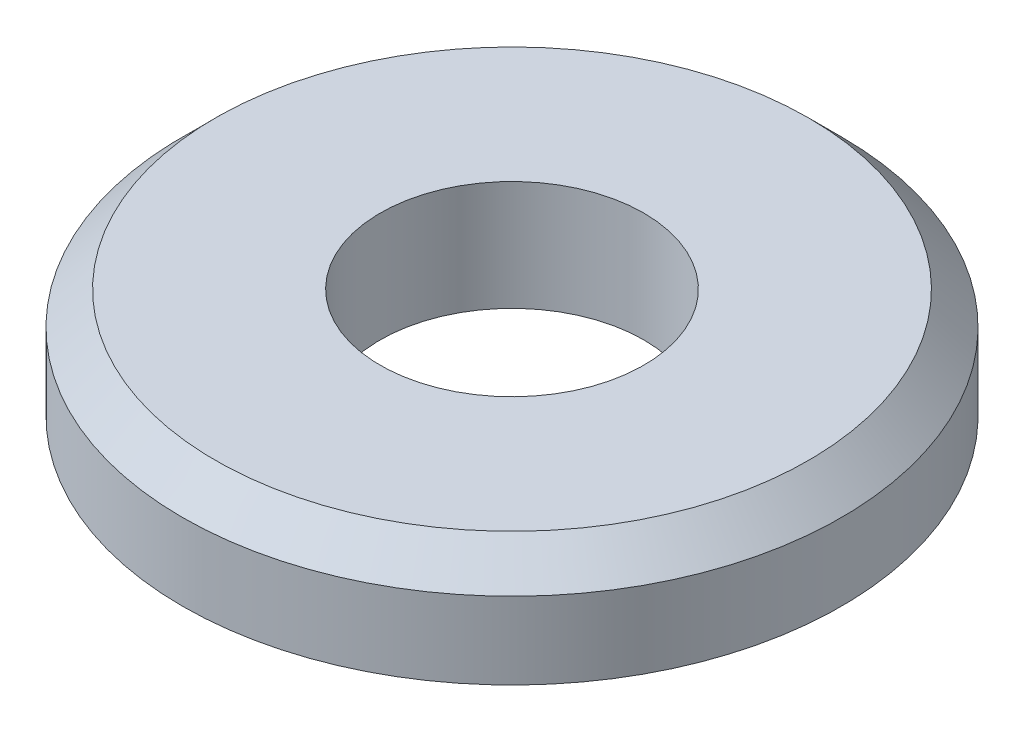
SolidWorks part; units mm, degrees
material "Stainless Steel (ferritic)"
ref_plane "Front Plane" through (0, 0, 0) normal (0, 0, 1) x (1, 0, 0)
ref_plane "Top Plane" through (0, 0, 0) normal (0, 1, 0) x (1, 0, 0)
ref_plane "Right Plane" through (0, 0, 0) normal (1, 0, 0) x (0, 0, -1)
sketch "Sketch1" plane through (0, 0, 0) normal (1, 0, 0) x (0, 0, -1)
  line L0 (0, 0) -> (0, 15.2034) construction
  line L1 (6, 0) -> (6, 5)
  line L2 (6, 5) -> (13.5, 5)
  line L3 (13.5, 5) -> (15, 3.5)
  line L4 (15, 3.5) -> (15, 0)
  line L5 (15, 0) -> (6, 0)
  dimension "D1" = 30
  dimension "D2" = 5
  dimension "D3" = 12
  dimension "D4" = 1.5
  dimension "D5" = 45
revolve "Revolve1" add sketch "Sketch1" angle 360 about L0
